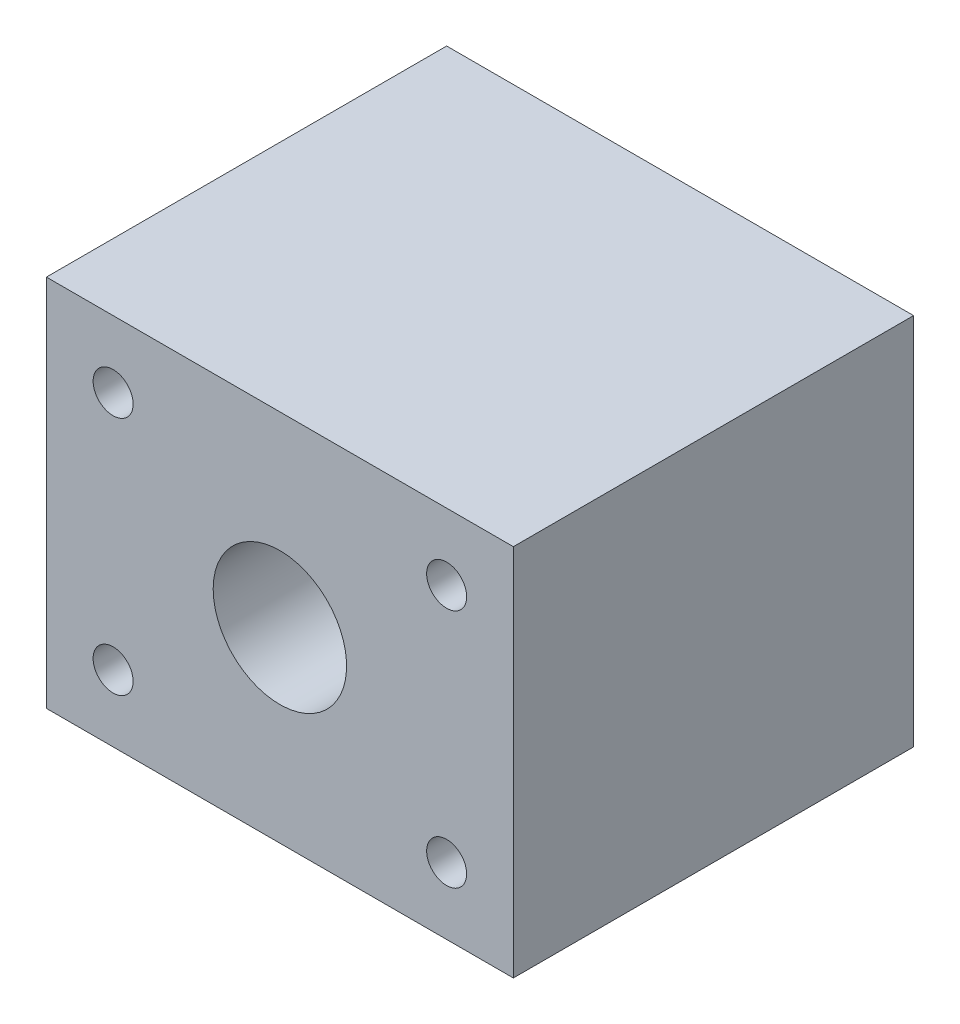
SolidWorks part; units mm, degrees
ref_plane "Front Plane" through (0, 0, 0) normal (0, 0, 1) x (1, 0, 0)
ref_plane "Top Plane" through (0, 0, 0) normal (0, 1, 0) x (1, 0, 0)
ref_plane "Right Plane" through (0, 0, 0) normal (1, 0, 0) x (0, 0, -1)
sketch "Sketch1" plane through (0, 0, 0) normal (0, 1, 0) x (1, 0, 0)
  line L1 (-17.5, -15) -> (17.5, -15)
  line L2 (-17.5, -15) -> (-17.5, 15)
  line L3 (-17.5, 15) -> (17.5, 15)
  line L4 (17.5, -15) -> (17.5, 15)
  line L5 (-17.5, -15) -> (17.5, 15) construction
  line L6 (-17.5, 15) -> (17.5, -15) construction
  point P0 (0, 0)
  dimension "D1" = 35
  dimension "D2" = 30
extrude "Boss-Extrude1" add sketch "Sketch1" along normal blind 28
sketch "Sketch2" plane through (0, 0, 15) normal (0, 0, 1) x (1, 0, 0)
  line L0 (-17.5, 28) -> (17.5, 28) construction
  line L1 (-17.5, 28) -> (-17.5, 0) construction
  line L2 (17.5, 28) -> (17.5, 0) construction
  line L3 (-17.5, 0) -> (17.5, 0) construction
  circle A0 centre (-12.5, 23) radius 1.5
  circle A1 centre (12.5, 23) radius 1.5
  circle A2 centre (12.5, 5) radius 1.5
  circle A3 centre (-12.5, 5) radius 1.5
  point P10 (0, 0)
  point P12 (0, 0)
  dimension "D1" = 3
  dimension "D4" = 5
  dimension "D2" = 5
  dimension "D3" = 5
  dimension "D5" = 5
  dimension "D6" = 5
  dimension "D7" = 5
  dimension "D8" = 5
  dimension "D9" = 5
extrude "Cut-Extrude1" cut sketch "Sketch2" against normal blind 10
sketch "Sketch3" plane through (0, 0, -15) normal (0, 0, -1) x (-1, 0, 0)
  line L0 (-17.5, 28) -> (17.5, 28) construction
  circle A0 centre (0, 14) radius 11
  dimension "D1" = 14
extrude "Cut-Extrude2" cut sketch "Sketch3" against normal blind 5
sketch "Sketch4" plane through (0, 0, -10) normal (0, 0, -1) x (-1, 0, 0)
  line L0 (17.5, 28) -> (17.5, 0) construction
  line L1 (-17.5, 28) -> (17.5, 28) construction
  circle A0 centre (0, 14) radius 5
  dimension "D1" = 17.5
  dimension "D2" = 14
extrude "Cut-Extrude3" cut sketch "Sketch4" against normal through all
